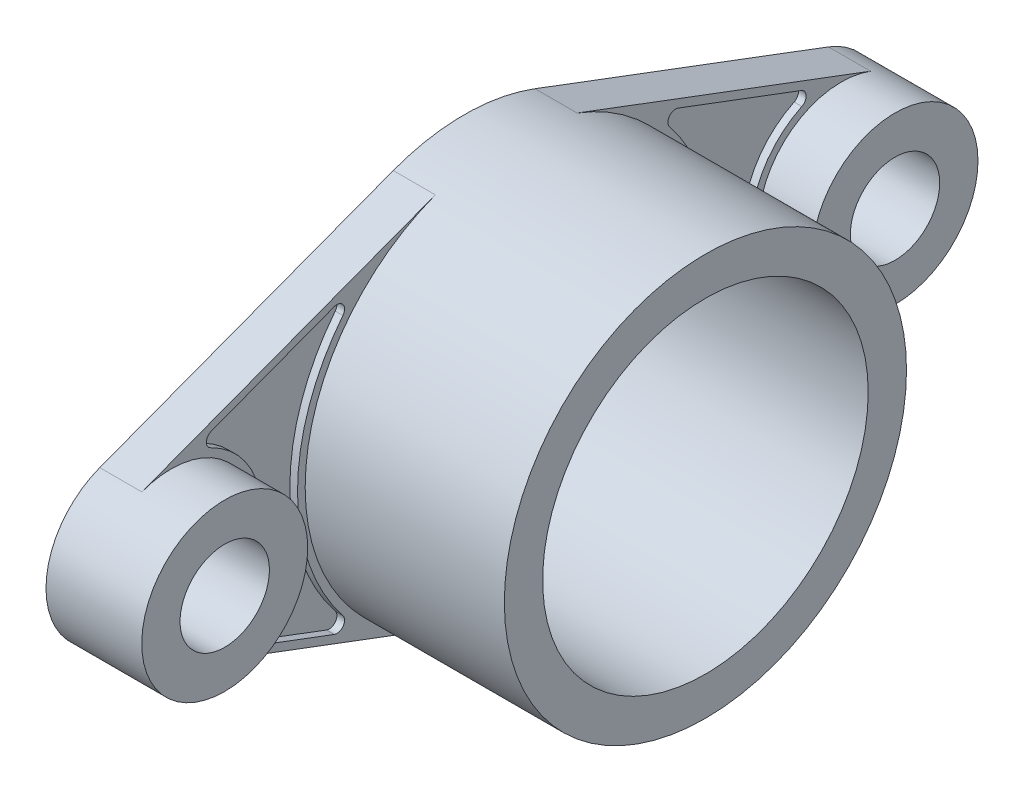
SolidWorks part; units mm, degrees
material "Polybutadiene (PB)"
ref_plane "Front Plane" through (0, 0, 0) normal (0, 0, 1) x (1, 0, 0)
ref_plane "Top Plane" through (0, 0, 0) normal (0, 1, 0) x (1, 0, 0)
ref_plane "Right Plane" through (0, 0, 0) normal (1, 0, 0) x (0, 0, -1)
sketch "Sketch1" plane through (0, 0, 0) normal (1, 0, 0) x (0, 0, -1)
  line L0 (-87.5, 0) -> (87.5, 0)
  line L1 (-95.1349, 20.2769) -> (-18.5, 49.1325)
  line L2 (18.5, 49.1325) -> (95.1349, 20.2769)
  line L3 (-95.1349, -20.2769) -> (-18.5, -49.1325)
  line L4 (95.1349, -20.2769) -> (18.5, -49.1325)
  circle A0 centre (0, 0) radius 42.5
  circle A1 centre (0, 0) radius 52.5
  circle A2 centre (87.5, 0) radius 21.6667
  circle A3 centre (87.5, 0) radius 11.6667
  circle A4 centre (-87.5, 0) radius 21.6667
  circle A5 centre (-87.5, 0) radius 11.6667
  point P12 (0, 0)
  point P18 (0, 0)
  dimension "D2" = 23.3333
  dimension "D4" = 105
  dimension "D1" = 10
  dimension "D3" = 175
  dimension "D5" = 10
extrude "Boss-Extrude1" add sketch "Sketch1" along normal blind 25
sketch "Sketch2" plane through (25, 0, 0) normal (1, 0, 0) x (0, 0, -1)
  circle A0 centre (0, 0) radius 42.5 construction
  circle A1 centre (0, 0) radius 52.5
  circle A2 centre (0, 0) radius 52.5
  circle A3 centre (0, 0) radius 42.5
  dimension "D1" = 0
extrude "Boss-Extrude2" add sketch "Sketch2" along normal blind 38
sketch "Sketch4" plane through (0, 0, 0) normal (1, 0, 0) x (0, 0, -1)
  line L0 (18.5, 49.1325) -> (95.1349, 20.2769) construction
  line L1 (95.1349, -20.2769) -> (18.5, -49.1325) construction
  line L2 (-95.1349, -20.2769) -> (-18.5, -49.1325) construction
  line L3 (-95.1349, 20.2769) -> (-18.5, 49.1325) construction
  line L4 (18.5, 49.1325) -> (95.1349, 20.2769)
  line L5 (95.1349, -20.2769) -> (18.5, -49.1325)
  line L6 (-95.1349, -20.2769) -> (-18.5, -49.1325)
  line L7 (-95.1349, 20.2769) -> (-18.5, 49.1325)
  circle A0 centre (87.5, 0) radius 21.6667 construction
  circle A1 centre (0, 0) radius 52.5 construction
  circle A2 centre (-87.5, 0) radius 21.6667 construction
  arc A3 (95.1349, 20.2769) -> (95.1349, -20.2769) centre (87.5, 0) ccw
  arc A4 (-18.5, 49.1325) -> (-18.5, -49.1325) centre (0, 0) ccw
  arc A5 (-95.1349, -20.2769) -> (-95.1349, 20.2769) centre (-87.5, 0) ccw
  arc A6 (18.5, -49.1325) -> (18.5, 49.1325) centre (0, 0) ccw
extrude "Boss-Extrude3" add sketch "Sketch4" along normal blind 11
sketch "Sketch5" plane through (11, 0, 0) normal (1, 0, 0) x (0, 0, -1)
  line L8 (-94.4302, -18.4052) -> (-17.7952, -47.2608)
  line L9 (-77.0055, -24.9662) -> (-44.9189, -37.0478)
  line L18 (94.4302, 18.4052) -> (17.7952, 47.2608)
  line L19 (77.0055, 24.9662) -> (44.9189, 37.0478)
  line L21 (17.7952, -47.2608) -> (94.4302, -18.4052)
  line L22 (44.9189, -37.0478) -> (77.0055, -24.9662)
  line L23 (-17.7952, 47.2608) -> (-94.4302, 18.4052)
  line L24 (-44.9189, 37.0478) -> (-77.0055, 24.9662)
  arc A0 (42.6491, -33.9309) -> (42.6491, 33.9309) centre (0, 0) ccw
  arc A2 (-77.1734, -21.2949) -> (-77.1734, 21.2949) centre (-87.5, 0) ccw
  circle A3 centre (0, 0) radius 52.5 construction
  arc A4 (-95.1349, -20.2769) -> (-95.1349, 20.2769) centre (-87.5, 0) ccw construction
  arc A5 (77.1734, 21.2949) -> (77.1734, -21.2949) centre (87.5, 0) ccw
  circle A6 centre (87.5, 0) radius 21.6667 construction
  arc A7 (-42.6491, 33.9309) -> (-42.6491, -33.9309) centre (0, 0) ccw
  arc A8 (-77.1734, 21.2949) -> (-77.0055, 24.9662) centre (-76.3007, 23.0944) cw
  arc A9 (-44.9189, -37.0478) -> (-42.6491, -33.9309) centre (-44.2142, -35.1761) ccw
  arc A10 (-77.1734, -21.2949) -> (-77.0055, -24.9662) centre (-76.3007, -23.0944) ccw
  arc A11 (-42.6491, 33.9309) -> (-44.9189, 37.0478) centre (-44.2142, 35.1761) ccw
  arc A12 (44.9189, -37.0478) -> (42.6491, -33.9309) centre (44.2142, -35.1761) cw
  arc A13 (77.0055, -24.9662) -> (77.1734, -21.2949) centre (76.3007, -23.0944) ccw
  arc A14 (77.1734, 21.2949) -> (77.0055, 24.9662) centre (76.3007, 23.0944) ccw
  arc A15 (44.9189, 37.0478) -> (42.6491, 33.9309) centre (44.2142, 35.1761) ccw
  dimension "D8" = 2
  dimension "D9" = 2
  dimension "D10" = 2
  dimension "D11" = 2
  dimension "D12" = 2
  dimension "D13" = 2
  dimension "D14" = 2
  dimension "D15" = 2
  dimension "D1" = 2
  dimension "D2" = 2
  dimension "D3" = 2
  dimension "D5" = 2
  dimension "D6" = 2
  dimension "D7" = 2
  dimension "D4" = 2
extrude "Cut-Extrude1" cut sketch "Sketch5" against normal blind 2
equation "\"A\" = 35"
equation "\"B\" = 10"
equation "\"C\"= 2"
equation "\"D1@Sketch1\"=\"B\""
equation "\"D2@Sketch1\"=\"A\"*2/3"
equation "\"D3@Sketch1\"=\"A\"*5"
equation "\"D5@Sketch1\"=\"B\""
equation "\"D4@Sketch1\"=\"A\"*3"
equation "\"D1@Boss-Extrude3\"=\"C\"+9"
equation "\"D1@Sketch5\"=\"C\""
equation "\"D2@Sketch5\"=\"C\""
equation "\"D3@Sketch5\"=\"C\""
equation "\"D4@Sketch5\"=\"C\""
equation "\"D6@Sketch5\"=\"C\""
equation "\"D7@Sketch5\"=\"C\""
equation "\"D5@Sketch5\"=\"C\""
equation "\"D1@Cut-Extrude1\"=\"C\""
equation "\"D8@Sketch5\"=\"C\""
equation "\"D11@Sketch5\"=\"C\""
equation "\"D10@Sketch5\"=\"C\""
equation "\"D9@Sketch5\"=\"C\""
equation "\"D12@Sketch5\"=\"C\""
equation "\"D13@Sketch5\"=\"C\""
equation "\"D14@Sketch5\"=\"C\""
equation "\"D15@Sketch5\"=\"C\""
